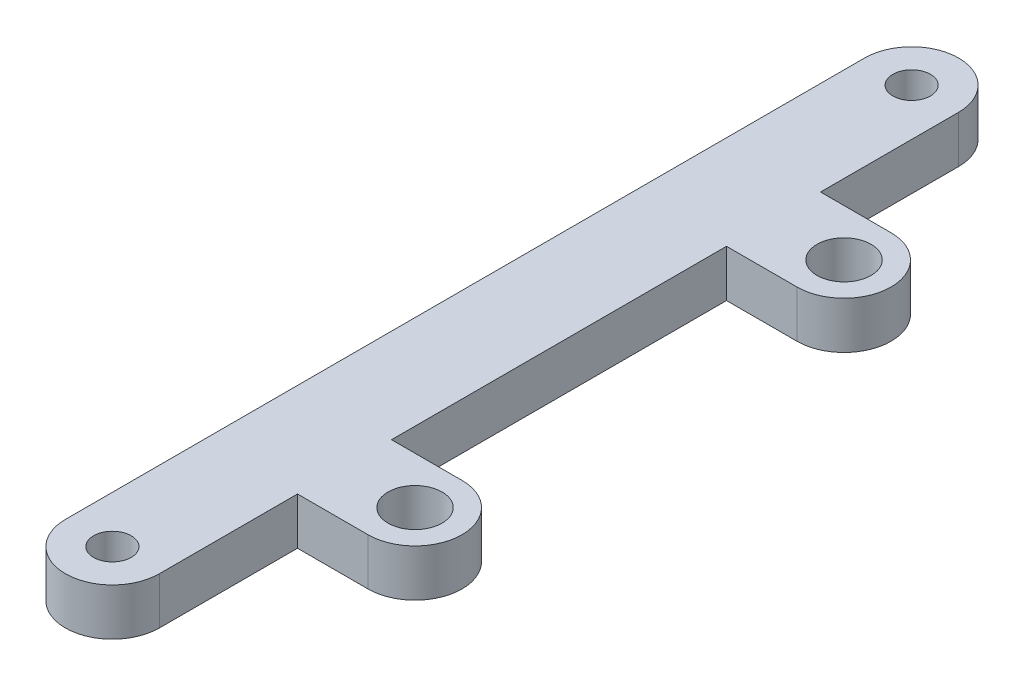
SolidWorks part; units mm, degrees
ref_plane "Front Plane" through (0, 0, 0) normal (0, 0, 1) x (1, 0, 0)
ref_plane "Top Plane" through (0, 0, 0) normal (0, 1, 0) x (1, 0, 0)
ref_plane "Right Plane" through (0, 0, 0) normal (1, 0, 0) x (0, 0, -1)
sketch "Sketch1" plane through (0, 0, 0) normal (0, 1, 0) x (1, 0, 0)
  line L0 (0, 0) -> (0, 68) construction
  line L1 (-4, 68) -> (-4, 0)
  line L2 (4, 68) -> (4, 56.25)
  line L3 (0, 34) -> (10, 34) construction
  line L4 (10, 34) -> (10, 52.25) construction
  line L5 (10, 56.25) -> (4, 56.25)
  line L6 (10, 48.25) -> (4, 48.25)
  line L7 (4, 48.25) -> (4, 19.75)
  line L8 (10, 19.75) -> (4, 19.75)
  line L9 (10, 11.75) -> (4, 11.75)
  line L10 (4, 11.75) -> (4, 0)
  circle A0 centre (0, 68) radius 1.6
  arc A1 (4, 68) -> (-4, 68) centre (0, 68) ccw
  circle A2 centre (0, 0) radius 1.6
  arc A3 (-4, 0) -> (4, 0) centre (0, 0) ccw
  arc A4 (10, 48.25) -> (10, 56.25) centre (10, 52.25) ccw
  circle A5 centre (10, 52.25) radius 2.3
  circle A6 centre (10, 15.75) radius 2.3
  arc A7 (10, 19.75) -> (10, 11.75) centre (10, 15.75) cw
extrude "Boss-Extrude1" add sketch "Sketch1" along normal blind 4
